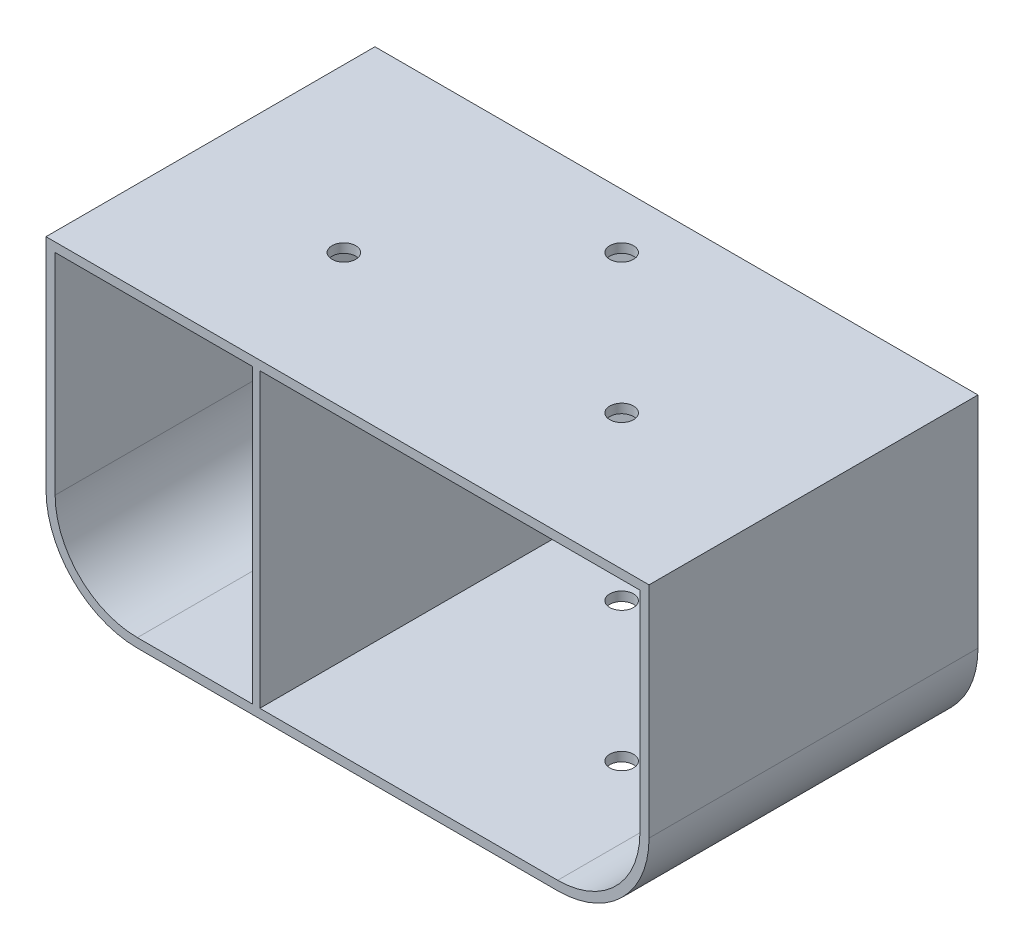
SolidWorks part; units mm, degrees
ref_plane "Přední rovina" through (0, 0, 0) normal (0, 0, 1) x (1, 0, 0)
ref_plane "Horní rovina" through (0, 0, 0) normal (0, 1, 0) x (1, 0, 0)
ref_plane "Pravá rovina" through (0, 0, 0) normal (1, 0, 0) x (0, 0, -1)
sketch "Skica1" plane through (0, 0, 0) normal (0, 0, 1) x (1, 0, 0)
  line L1 (-82.5, 42.5) -> (82.5, 42.5)
  line L2 (-82.5, 42.5) -> (-82.5, -17.5)
  line L3 (-57.5, -42.5) -> (57.5, -42.5)
  line L4 (82.5, 42.5) -> (82.5, -17.5)
  line L5 (-82.5, 42.5) -> (82.5, -42.5) construction
  line L6 (-82.5, -42.5) -> (82.5, 42.5) construction
  arc A0 (57.5, -42.5) -> (82.5, -17.5) centre (57.5, -17.5) ccw
  arc A1 (-82.5, -17.5) -> (-57.5, -42.5) centre (-57.5, -17.5) ccw
  point P0 (0, 0)
  dimension "D3" = 25
  dimension "D1" = 165
  dimension "D2" = 85
extrude "Přidat vysunutím1" add sketch "Skica1" along normal blind 90
sketch "Skica2" plane through (0, 0, 90) normal (0, 0, 1) x (1, 0, 0)
  line L0 (-82.5, 42.5) -> (82.5, 42.5)
  line L1 (-82.5, 42.5) -> (-82.5, -17.5)
  line L2 (-57.5, -42.5) -> (57.5, -42.5)
  line L3 (82.5, 42.5) -> (82.5, -17.5)
  line L4 (-82.5, 42.5) -> (82.5, -42.5) construction
  line L5 (-82.5, -42.5) -> (82.5, 42.5) construction
  line L6 (80, 40) -> (80, -17.5)
  line L7 (-57.5, -40) -> (57.5, -40)
  line L8 (-80, 40) -> (-80, -17.5)
  line L9 (-80, 40) -> (80, 40)
  line L10 (-26, -40) -> (-26, 40)
  line L11 (-24, 40) -> (-24, -40)
  arc A0 (57.5, -42.5) -> (82.5, -17.5) centre (57.5, -17.5) ccw
  arc A1 (-82.5, -17.5) -> (-57.5, -42.5) centre (-57.5, -17.5) ccw
  arc A2 (57.5, -40) -> (80, -17.5) centre (57.5, -17.5) ccw
  arc A3 (-80, -17.5) -> (-57.5, -40) centre (-57.5, -17.5) ccw
  point P0 (0, 0)
  dimension "D2" = 160
  dimension "D3" = 54
  dimension "D4" = 2
  dimension "D1" = 2.5
extrude "Odebrat vysunutím1" cut sketch "Skica2" against normal blind 87 contours L7 A2 L6 L9 L11 | L8 A3 L7 L10 L9
sketch "Skica3" plane through (0, 42.5, 0) normal (0, 1, 0) x (1, 0, 0)
  line L0 (0, 0) -> (0, -90)
  line L1 (82.5, 0) -> (-82.5, 0) construction
  line L2 (82.5, -90) -> (-82.5, -90) construction
  line L3 (-82.5, -53) -> (82.5, -53)
  line L4 (-82.5, -90) -> (-82.5, 0) construction
  line L5 (82.5, -90) -> (82.5, 0) construction
  point P6 (0, -15)
  point P13 (38, -53)
  point P14 (-38, -53)
  dimension "D1" = 15
  dimension "D2" = 38
  dimension "D3" = 38
  dimension "D4" = 38
hole_wizard "Díry pro kolík, velikost mm1" positions "Skica4" profile "Skica5" hole size "Ø6.0" standard "ANSI Metric" end condition through all
sketch "Skica4" plane through (0, 42.5, 0) normal (0, 1, 0) x (1, 0, 0)
  point P0 (0, -15)
  point P3 (38, -53)
  point P6 (-38, -53)
sketch "Skica5" plane through (0, 42.5, 15) normal (1, 0, 0) x (0, 0, 1)
  line L0 (0, 0) -> (0, 85)
  line L1 (0, 85) -> (3.25, 85)
  line L2 (3.25, 85) -> (3.25, 0)
  line L5 (3.25, 0) -> (0, 0)
  line L11 (0, -6.35) -> (0, 107.95) construction
  dimension "Průměr díry skrz" = 6.5
  dimension "Hloubka díry skrz" = 85
